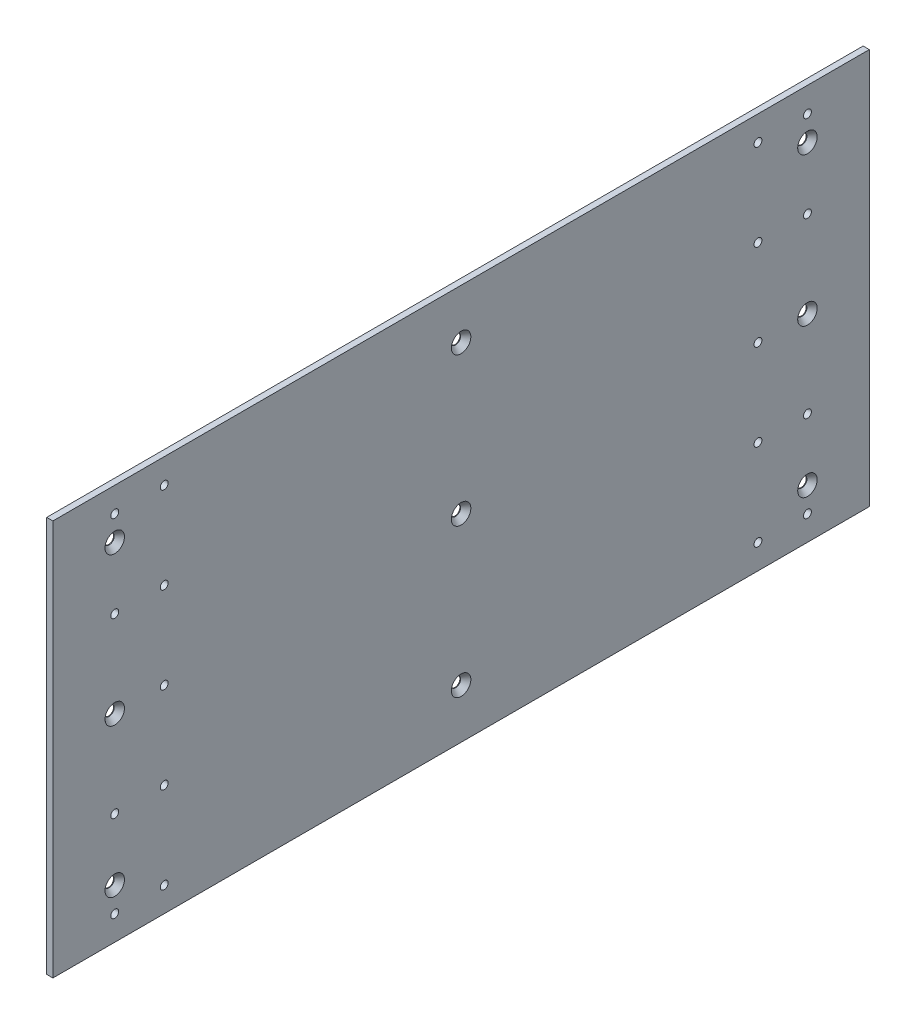
SolidWorks part; units mm, degrees
material "2024-T4"
ref_plane "Front Plane" through (0, 0, 0) normal (0, 0, 1) x (1, 0, 0)
ref_plane "Top Plane" through (0, 0, 0) normal (0, 1, 0) x (1, 0, 0)
ref_plane "Right Plane" through (0, 0, 0) normal (1, 0, 0) x (0, 0, -1)
sketch "Sketch1" plane through (0, 0, 0) normal (1, 0, 0) x (0, 0, -1)
  line L1 (-222.5531, -128.5307) -> (196.5469, -128.5307)
  line L2 (-222.5531, -128.5307) -> (-222.5531, 74.6693)
  line L3 (-222.5531, 74.6693) -> (196.5469, 74.6693)
  line L4 (196.5469, -128.5307) -> (196.5469, 74.6693)
  dimension "D1" = 419.1
  dimension "D2" = 203.2
extrude "Boss-Extrude1" add sketch "Sketch1" along normal blind 3.175
sketch "Sketch3" plane through (3.175, 0, 0) normal (1, 0, 0) x (0, 0, -1)
  line L0 (-13.0031, -128.5307) -> (-13.0031, 74.6693)
  line L3 (-222.5531, -128.5307) -> (196.5469, -128.5307) construction
  line L4 (196.5469, 74.6693) -> (-222.5531, 74.6693) construction
  circle A0 centre (-190.8031, 49.2693) radius 2.5527
  circle A1 centre (-190.8031, -26.9307) radius 2.5527
  circle A2 centre (-190.8031, -103.1307) radius 2.5527
  circle A3 centre (-13.0031, -103.1307) radius 2.5527
  circle A4 centre (164.7969, -103.1307) radius 2.5527
  circle A5 centre (164.7969, -26.9307) radius 2.5527
  circle A6 centre (164.7969, 49.2693) radius 2.5527
  circle A7 centre (-13.0031, 49.2693) radius 2.5527
  circle A8 centre (-13.0031, -26.9307) radius 2.5527
  dimension "D11" = 5.1054
  dimension "D7" = 5.1054
  dimension "D8" = 5.1054
  dimension "D9" = 5.1054
  dimension "D10" = 5.1054
  dimension "D12" = 5.1054
  dimension "D1" = 209.55
  dimension "D2" = 209.55
  dimension "D3" = 209.55
  dimension "D4" = 177.8
  dimension "D5" = 177.8
  dimension "D6" = 177.8
  dimension "D13" = 25.4
  dimension "D14" = 76.2
  dimension "D15" = 76.2
hole_wizard "CSK for #10 Flat Head Machine Screw1" positions "Sketch7" profile "Sketch6" countersink size "#10" standard "ANSI Inch" end condition through all
sketch "Sketch7" plane through (3.175, 0, 0) normal (1, 0, 0) x (0, 0, -1)
  point P0 (-190.8031, 49.2693)
  point P3 (-190.8031, -26.9307)
  point P6 (-190.8031, -103.1307)
  point P9 (-13.0031, 49.2693)
  point P12 (-13.0031, -26.9307)
  point P15 (-13.0031, -103.1307)
  point P18 (164.7969, -26.9307)
  point P21 (164.7969, -103.1307)
sketch "Sketch6" plane through (3.175, 49.2693, 190.8031) normal (0, 1, 0) x (0, 0, -1)
  line L0 (0, 0) -> (0, 3.175)
  line L1 (0, 3.175) -> (2.5527, 3.175)
  line L2 (2.5527, 3.175) -> (2.5527, 2.8152)
  line L3 (2.5527, 2.8152) -> (4.9999, 0)
  line L5 (4.9999, 0) -> (0, 0)
  line L6 (-2.5527, 2.8152) -> (-4.9999, 0) construction
  line L11 (0, -6.35) -> (0, 107.95) construction
  dimension "Thru Hole Dia." = 5.1054
  dimension "Thru Hole Depth" = 3.175
  dimension "Near C'Sink Dia." = 9.9998
  dimension "Near C'Sink Angle" = 82
hole_wizard "CSK for #10 Flat Head Machine Screw2" positions "Sketch9" profile "Sketch8" countersink size "#10" standard "ANSI Inch" end condition through all
sketch "Sketch9" plane through (3.175, 0, 0) normal (1, 0, 0) x (0, 0, -1)
  point P0 (164.7969, 49.2693)
sketch "Sketch8" plane through (3.175, 49.2693, -164.7969) normal (0, 1, 0) x (0, 0, -1)
  line L0 (0, 0) -> (0, 3.175)
  line L1 (0, 3.175) -> (2.5527, 3.175)
  line L2 (2.5527, 3.175) -> (2.5527, 2.8152)
  line L3 (2.5527, 2.8152) -> (4.9999, 0)
  line L5 (4.9999, 0) -> (0, 0)
  line L6 (-2.5527, 2.8152) -> (-4.9999, 0) construction
  line L11 (0, -6.35) -> (0, 107.95) construction
  dimension "Thru Hole Dia." = 5.1054
  dimension "Thru Hole Depth" = 3.175
  dimension "Near C'Sink Dia." = 9.9998
  dimension "Near C'Sink Angle" = 82
hole_wizard "#10-32 Tapped Hole1" positions "Sketch10" profile "Sketch11" tap size "#10-32" standard "ANSI Inch"
sketch "Sketch10" plane through (3.175, 3.5415, 145.2035) normal (1, 0, 0) x (0, 0, -1)
  point P0 (284.6004, 58.4279)
  point P3 (310.0004, 58.4279)
  point P6 (284.6004, 13.9779)
  point P9 (310.0004, 13.9779)
  point P12 (284.6004, -30.4721)
  point P15 (284.6004, -74.9221)
  point P18 (310.0004, -74.9221)
  point P21 (284.6004, -119.3721)
  point P24 (310.0004, -119.3721)
  point P27 (-20.1996, 58.4279)
  point P30 (-45.5996, 58.4279)
  point P33 (-20.1996, 13.9779)
  point P36 (-45.5996, 13.9779)
  point P39 (-20.1996, -30.4721)
  point P42 (-20.1996, -74.9221)
  point P45 (-45.5996, -74.9221)
  point P48 (-45.5996, -119.3721)
  point P51 (-20.1996, -119.3721)
sketch "Sketch11" plane through (3.175, 61.9693, -139.3969) normal (0, 1, 0) x (0, 0, -1)
  line L0 (0, 0) -> (0, 18.9933)
  line L1 (0, 18.9933) -> (2.0193, 17.78)
  line L2 (2.0193, 17.78) -> (2.0193, 0)
  line L3 (2.0193, 0) -> (0, 0)
  line L4 (0, 18.9933) -> (-2.0193, 17.78) construction
  line L5 (0, -6.35) -> (0, 107.95) construction
  dimension "Tap Drill Dia." = 4.0386
  dimension "Tap Drill Depth" = 17.78
  dimension "Drill Angle" = 118
cosmetic thread "Hole Thread1" parameters "D1"=3.175, "D2"=4.826
cosmetic thread "Hole Thread2" parameters "D1"=3.175, "D2"=4.826
cosmetic thread "Hole Thread3" parameters "D1"=3.175, "D2"=4.826
cosmetic thread "Hole Thread4" parameters "D1"=3.175, "D2"=4.826
cosmetic thread "Hole Thread5" parameters "D1"=3.175, "D2"=4.826
cosmetic thread "Hole Thread6" parameters "D1"=3.175, "D2"=4.826
cosmetic thread "Hole Thread7" parameters "D1"=3.175, "D2"=4.826
cosmetic thread "Hole Thread8" parameters "D1"=3.175, "D2"=4.826
cosmetic thread "Hole Thread9" parameters "D1"=3.175, "D2"=4.826
cosmetic thread "Hole Thread10" parameters "D1"=3.175, "D2"=4.826
cosmetic thread "Hole Thread11" parameters "D1"=3.175, "D2"=4.826
cosmetic thread "Hole Thread12" parameters "D1"=3.175, "D2"=4.826
cosmetic thread "Hole Thread13" parameters "D1"=3.175, "D2"=4.826
cosmetic thread "Hole Thread14" parameters "D1"=3.175, "D2"=4.826
cosmetic thread "Hole Thread15" parameters "D1"=3.175, "D2"=4.826
cosmetic thread "Hole Thread16" parameters "D1"=3.175, "D2"=4.826
cosmetic thread "Hole Thread18" parameters "D1"=3.175, "D2"=4.826
cosmetic thread "Hole Thread19" parameters "D1"=3.175, "D2"=4.826
